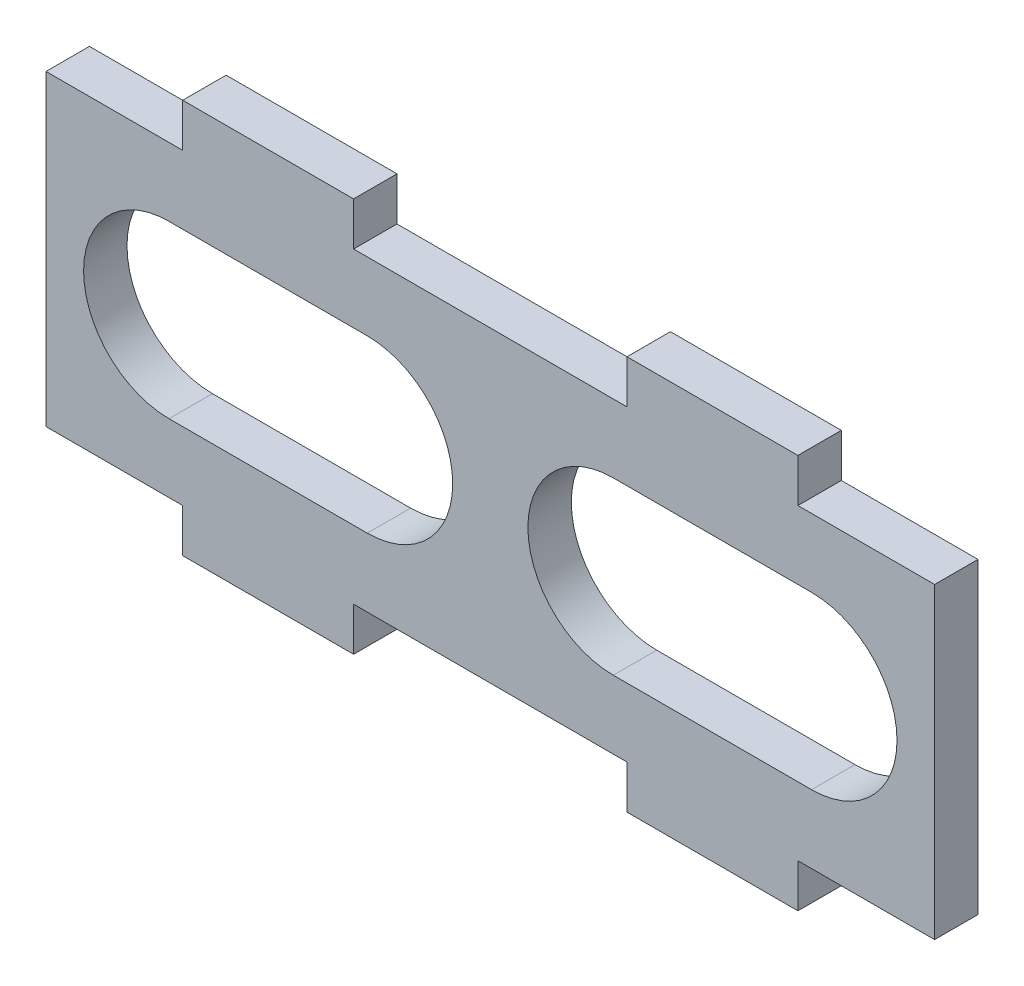
SolidWorks part; units mm, degrees
ref_plane "Plan de face" through (0, 0, 0) normal (0, 0, 1) x (1, 0, 0)
ref_plane "Plan de dessus" through (0, 0, 0) normal (0, 1, 0) x (1, 0, 0)
ref_plane "Plan de droite" through (0, 0, 0) normal (1, 0, 0) x (0, 0, -1)
sketch "Esquisse1" plane through (0, 0, 0) normal (0, 0, 1) x (1, 0, 0)
  line L1 (-65, 0) -> (65, 0)
  line L2 (-65, 0) -> (-65, 45)
  line L3 (-65, 45) -> (65, 45)
  line L4 (65, 0) -> (65, 45)
  point P4 (0, 0)
  dimension "D1" = 45
  dimension "D2" = 130
extrude "Boss.-Extru.1" add sketch "Esquisse1" along normal blind 6.35
sketch "Esquisse2" plane through (0, 0, 6.35) normal (0, 0, 1) x (1, 0, 0)
  line L0 (-65, 22.5) -> (65, 22.5) construction
  line L1 (-65, 45) -> (-65, 0) construction
  line L2 (65, 0) -> (65, 45) construction
  line L3 (-47, 22.5) -> (-18, 22.5) construction
  line L4 (-47, 35) -> (-18, 35)
  line L5 (-47, 10) -> (-18, 10)
  line L6 (0, 22.5) -> (0, 0) construction
  line L7 (0, 0) -> (-65, 0) construction
  line L8 (-32.5, 0) -> (-32.5, 22.5) construction
  line L9 (47, 22.5) -> (18, 22.5) construction
  line L10 (47, 35) -> (18, 35)
  line L11 (47, 10) -> (18, 10)
  arc A0 (-47, 35) -> (-47, 10) centre (-47, 22.5) ccw
  arc A1 (-18, 10) -> (-18, 35) centre (-18, 22.5) ccw
  arc A2 (47, 35) -> (47, 10) centre (47, 22.5) cw
  arc A3 (18, 10) -> (18, 35) centre (18, 22.5) cw
  point P8 (-32.5, 22.5)
  point P22 (32.5, 22.5)
  dimension "D1" = 18
  dimension "D2" = 25
extrude "Enlèv. mat.-Extru.1" cut sketch "Esquisse2" against normal up to next
sketch "Esquisse3" plane through (0, 0, 6.35) normal (0, 0, 1) x (1, 0, 0)
  line L0 (65, 45) -> (-65, 45) construction
  line L1 (-45, 45) -> (-20, 45)
  line L2 (-45, 45) -> (-45, 51.35)
  line L3 (-45, 51.35) -> (-20, 51.35)
  line L4 (-20, 45) -> (-20, 51.35)
  line L5 (-32.5, 45) -> (-32.5, 35) construction
  line L6 (-18, 35) -> (-47, 35) construction
  line L7 (-65, 22.5) -> (-20.883, 22.5) construction
  line L8 (-65, 45) -> (-65, 0) construction
  line L9 (0, 0) -> (0, 27.7085) construction
  line L10 (-45, -6.35) -> (-20, -6.35)
  line L11 (-20, 0) -> (-20, -6.35)
  line L12 (-45, 0) -> (-20, 0)
  line L13 (-45, 0) -> (-45, -6.35)
  line L14 (45, 51.35) -> (20, 51.35)
  line L15 (20, 45) -> (20, 51.35)
  line L16 (45, 45) -> (20, 45)
  line L17 (45, 45) -> (45, 51.35)
  line L18 (45, 0) -> (45, -6.35)
  line L19 (45, 0) -> (20, 0)
  line L20 (20, 0) -> (20, -6.35)
  line L21 (45, -6.35) -> (20, -6.35)
  dimension "D1" = 6.35
  dimension "D2" = 25
extrude "Boss.-Extru.2" add sketch "Esquisse3" against normal up to surface (6.35 mm away) up to face at (-32.5, 22.5, 0)
